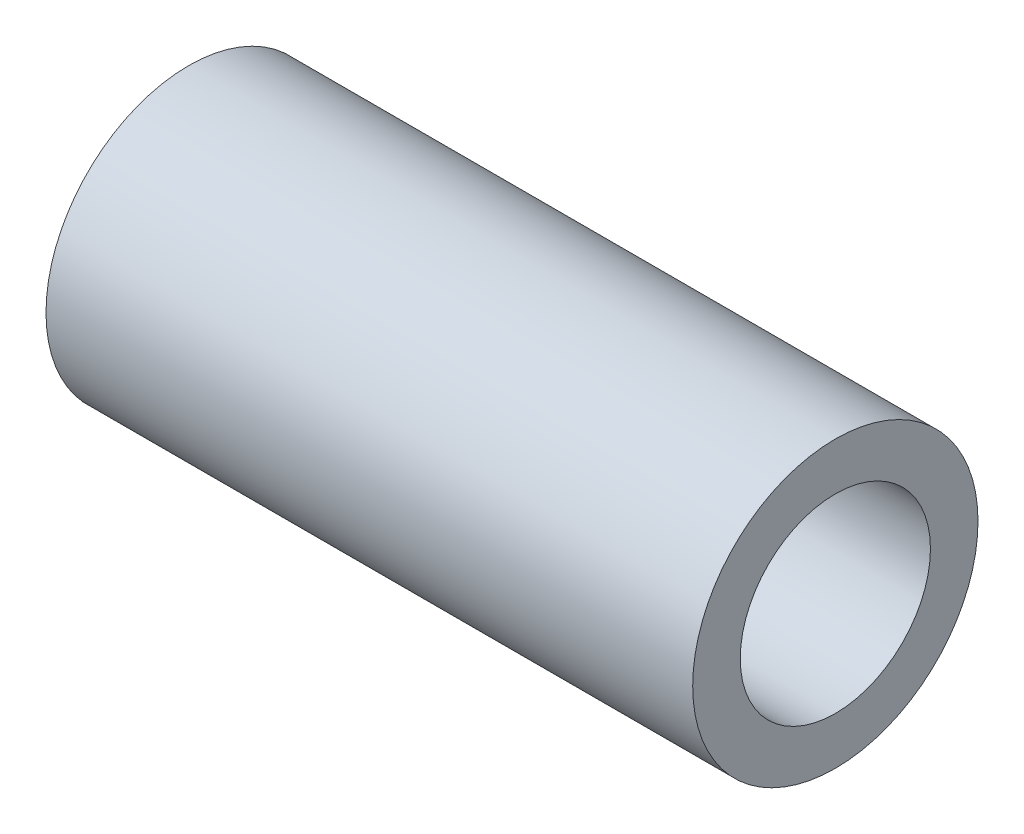
SolidWorks part; units mm, degrees
ref_plane "Front" through (0, 0, 0) normal (0, 0, 1) x (1, 0, 0)
ref_plane "Top" through (0, 0, 0) normal (0, 1, 0) x (1, 0, 0)
ref_plane "Right" through (0, 0, 0) normal (1, 0, 0) x (0, 0, -1)
sketch "Sketch1" plane through (0, 0, 0) normal (0, 0, 1) x (1, 0, 0)
  line L0 (-6.5008, 0) -> (27.0191, 0) construction
  line L2 (0, 0) -> (20.4, 0)
  line L3 (0, 0) -> (0, 4.5)
  line L4 (0, 4.5) -> (20.4, 4.5)
  line L5 (20.4, 0) -> (20.4, 4.5)
  dimension "D1" = 9
  dimension "D2" = 20.4
revolve "Revolve1" add sketch "Sketch1" angle 360 about L0
sketch "Sketch2" plane through (0, 0, 0) normal (0, 0, 1) x (1, 0, 0)
  line L0 (-3.0539, 0) -> (22.7009, 0) construction
  line L1 (20.4, -4.5) -> (20.4, 4.5) construction
  line L2 (0, 0) -> (20.4, 0)
  line L3 (0, 0) -> (0, 3)
  line L4 (0, 3) -> (20.4, 3)
  line L5 (20.4, 0) -> (20.4, 3)
  dimension "D1" = 6
revolve "Cut-Revolve1" cut sketch "Sketch2" angle 360 about L0
